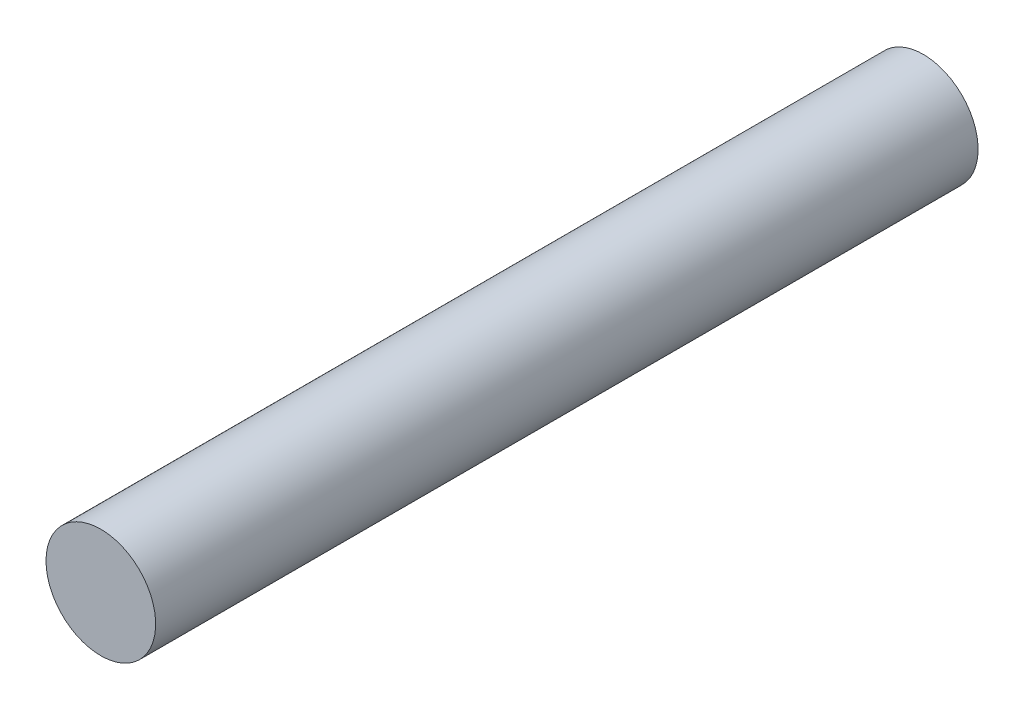
SolidWorks part; units mm, degrees
material "6061 Alloy"
ref_plane "Front Plane" through (0, 0, 0) normal (0, 0, 1) x (1, 0, 0)
ref_plane "Top Plane" through (0, 0, 0) normal (0, 1, 0) x (1, 0, 0)
ref_plane "Right Plane" through (0, 0, 0) normal (1, 0, 0) x (0, 0, -1)
sketch "Sketch1" plane through (0, 0, 0) normal (0, 0, 1) x (1, 0, 0)
  circle A0 centre (0, 0) radius 3
  dimension "D1" = 6
extrude "Boss-Extrude1" add sketch "Sketch1" along normal mid plane 45 contours A0
